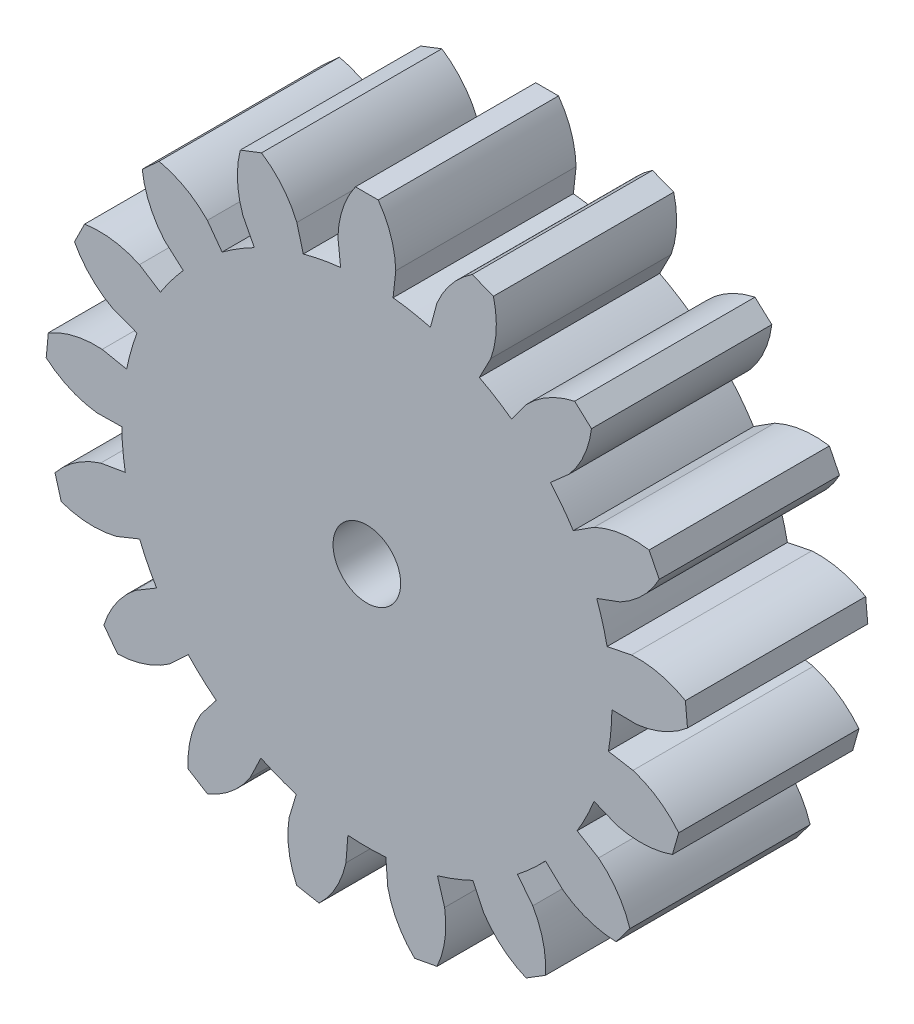
SolidWorks part; units mm, degrees
ref_plane "Front Plane" through (0, 0, 0) normal (0, 0, 1) x (1, 0, 0)
ref_plane "Top Plane" through (0, 0, 0) normal (0, 1, 0) x (1, 0, 0)
ref_plane "Right Plane" through (0, 0, 0) normal (1, 0, 0) x (0, 0, -1)
sketch "Sketch2" plane through (0, 0, 0) normal (0, 0, 1) x (1, 0, 0)
  circle A0 centre (0, 0) radius 10.875
  dimension "D1" = 21.75
extrude "Boss-Extrude1" add sketch "Sketch2" along normal blind 8
sketch "Sketch3" plane through (0, 0, 0) normal (0, 0, 1) x (1, 0, 0)
  line L0 (0, 0) -> (0, 35) construction
  line L2 (0, 0) -> (1.2831, 11.9121)
  line L3 (0, 0) -> (1.1764, 12.6956) construction
  line L5 (0, 0) -> (0.5055, 14.241) construction
  line L6 (0, 0) -> (-1.2831, 11.9121)
  line L7 (-0.5055, 14.241) -> (0.5055, 14.241)
  arc A0 (1.2831, 11.9121) -> (0.5055, 14.241) centre (-2.9231, 11.802) ccw
  arc A1 (-1.2831, 11.9121) -> (-0.5055, 14.241) centre (2.9231, 11.802) cw
  dimension "D5" = 1.011
  dimension "D1" = 35
  dimension "D2" = 11.981
  dimension "D3" = 12.75
  dimension "D4" = 14.25
extrude "Boss-Extrude2" add sketch "Sketch3" along normal blind 8
pattern_circular "CirPattern1" count 17 over 360 about axis through (0, 0, 0) along (0, 0, 1) of "Boss-Extrude2"
sketch "Sketch4" plane through (0, 0, 8) normal (0, 0, 1) x (1, 0, 0)
  circle A1 centre (0, 0) radius 1.5
  dimension "D1" = 3
extrude "Cut-Extrude1" cut sketch "Sketch4" against normal blind 8
